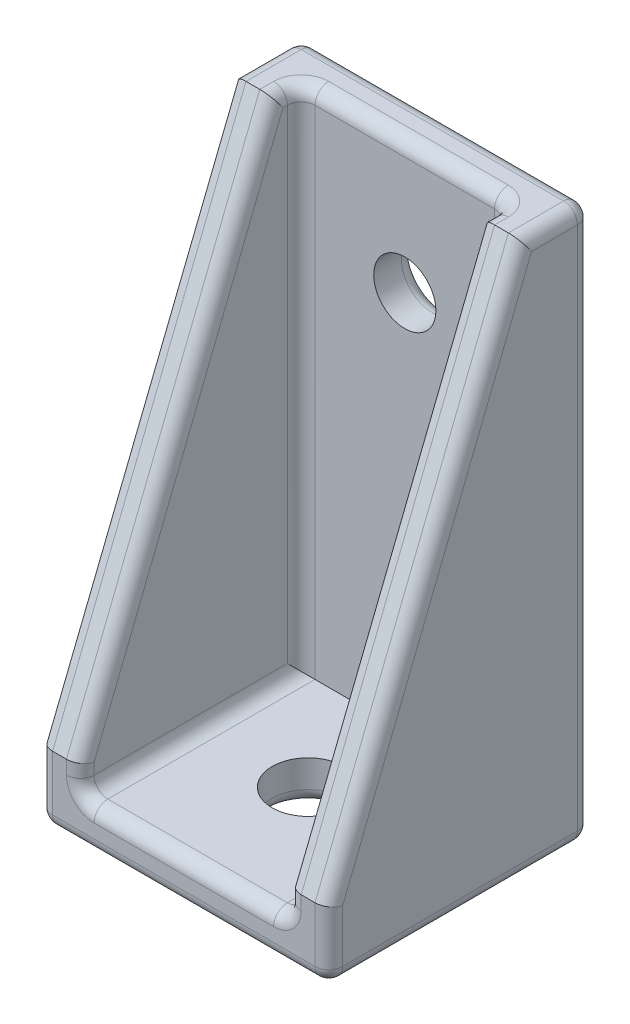
SolidWorks part; units mm, degrees
material "ABS"
ref_plane "Front Plane" through (0, 0, 0) normal (0, 0, 1) x (1, 0, 0)
ref_plane "Top Plane" through (0, 0, 0) normal (0, 1, 0) x (1, 0, 0)
ref_plane "Right Plane" through (0, 0, 0) normal (1, 0, 0) x (0, 0, -1)
sketch "Sketch2" plane through (0, 0, 0) normal (1, 0, 0) x (0, 0, -1)
  line L0 (0, 0) -> (0, 40)
  line L1 (0, 40) -> (-5, 40)
  line L2 (-5, 40) -> (-19, 5)
  line L3 (-19, 5) -> (-19, 0)
  line L4 (-19, 0) -> (0, 0)
  dimension "D1" = 40
  dimension "D2" = 19
  dimension "D3" = 5
  dimension "D4" = 5
extrude "Boss-Extrude1" add sketch "Sketch2" along normal blind 3
sketch "Sketch3" plane through (3, 0, 0) normal (1, 0, 0) x (0, 0, -1)
  line L0 (-19, 0) -> (-19, 3)
  line L1 (-19, 5) -> (-19, 0) construction
  line L2 (-19, 3) -> (-3, 3)
  line L3 (-3, 3) -> (-3, 40)
  line L4 (0, 40) -> (-5, 40) construction
  line L5 (-3, 40) -> (0, 40)
  line L6 (0, 40) -> (0, 0)
  line L7 (0, 0) -> (-19, 0)
  dimension "D1" = 3
  dimension "D2" = 3
extrude "Boss-Extrude2" add sketch "Sketch3" along normal blind 15
sketch "Sketch4" plane through (18, 0, 0) normal (1, 0, 0) x (0, 0, -1)
  line L5 (-19, 0) -> (0, 0)
  line L6 (-19, 5) -> (-19, 0)
  line L7 (-5, 40) -> (-19, 5)
  line L8 (0, 40) -> (-5, 40)
  line L9 (0, 0) -> (0, 40)
  line L10 (-19, 0) -> (0, 0)
  line L11 (-19, 5) -> (-19, 0)
  line L12 (-5, 40) -> (-19, 5)
  line L13 (0, 40) -> (-5, 40)
  line L14 (0, 0) -> (0, 40)
  dimension "D1" = 0
extrude "Boss-Extrude3" add sketch "Sketch4" along normal blind 3
sketch "Sketch5" plane through (0, 0, 0) normal (0, 0, -1) x (-1, 0, 0)
  line L0 (-10.5, 40) -> (-10.5, 0) construction
  line L1 (-21, 40) -> (0, 40) construction
  line L2 (-21, 0) -> (0, 0) construction
  circle A0 centre (-10.5, 30.5) radius 2.25
  dimension "D2" = 4.5
  dimension "D1" = 30.5
extrude "Cut-Extrude1" cut sketch "Sketch5" against normal up to surface (3 mm away) up to face at (12.375, 30.75, 3)
sketch "Sketch6" plane through (0, 0, 0) normal (0, -1, 0) x (1, 0, 0)
  line L0 (10.5, 0) -> (10.5, 19) construction
  line L1 (21, 0) -> (0, 0) construction
  line L2 (21, 19) -> (0, 19) construction
  circle A0 centre (10.5, 10) radius 2.6
  dimension "D1" = 10
  dimension "D2" = 5.2
extrude "Cut-Extrude2" cut sketch "Sketch6" against normal up to surface (3 mm away) up to face at (12.375, 3, 7)
fillet "Fillet1" radius 1 27 edges at (10.5, 0, 19) (10.5, 0, 7.4) (10.5, 0, 0) (10.5, 40, 0) (8.25, 30.5, 0) (3, 22.5, 12) (18, 22.5, 12) (0, 20, 0) (0, 40, 2.5) (0, 22.5, 12) (0, 2.5, 19) (0, 0, 9.5) (21, 0, 9.5) (21, 2.5, 19) (21, 22.5, 12) (21, 40, 2.5) (21, 20, 0)
